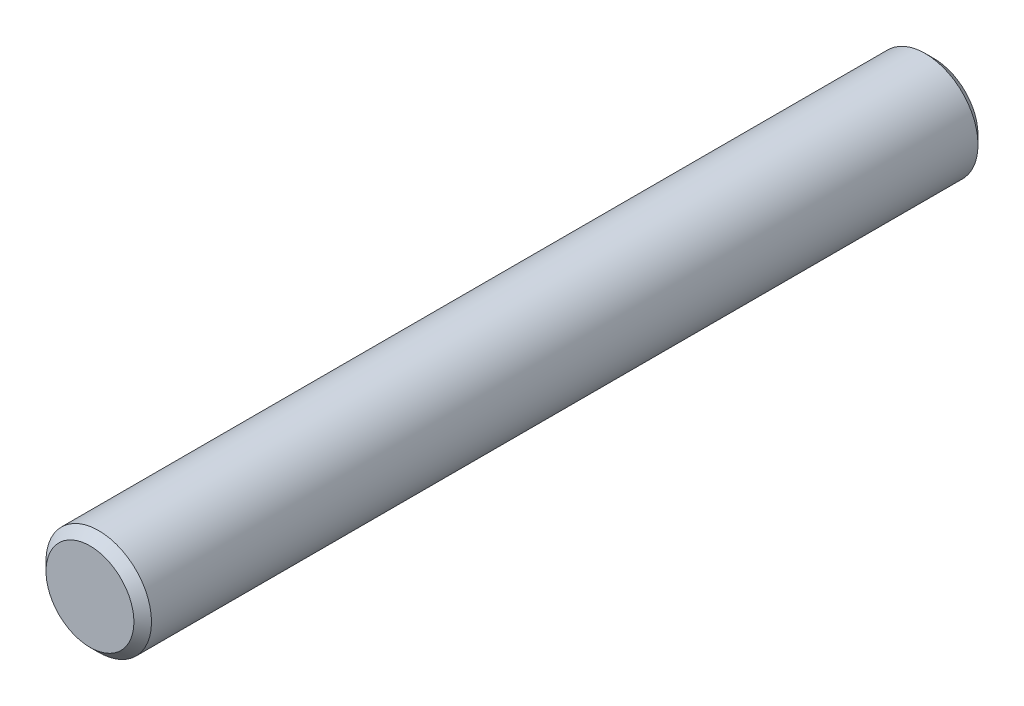
SolidWorks part; units mm, degrees
ref_plane "Front Plane" through (0, 0, 0) normal (0, 0, 1) x (1, 0, 0)
ref_plane "Top Plane" through (0, 0, 0) normal (0, 1, 0) x (1, 0, 0)
ref_plane "Right Plane" through (0, 0, 0) normal (1, 0, 0) x (0, 0, -1)
sketch "Sketch1" plane through (0, 0, 0) normal (0, 0, 1) x (1, 0, 0)
  circle A0 centre (0, 0) radius 1.5
  dimension "D1" = 3
extrude "Boss-Extrude1" add sketch "Sketch1" along normal blind 24
chamfer "Chamfer1" distance 0.25 angle 45 2 edges at (1.5, 0, 24) (1.5, 0, 0)
